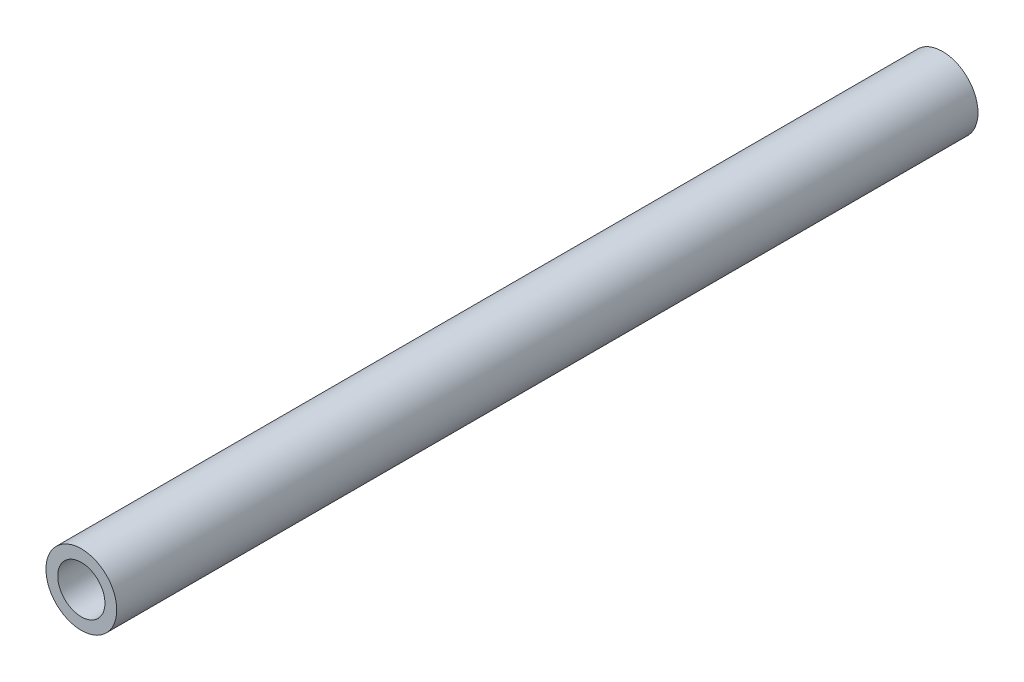
SolidWorks part; units mm, degrees
other "Ballast Support Tube 2 Left"
ref_plane "Front Plane" through (0, 0, 0) normal (0, 0, 1) x (1, 0, 0)
ref_plane "Top Plane" through (0, 0, 0) normal (0, 1, 0) x (1, 0, 0)
ref_plane "Right Plane" through (0, 0, 0) normal (1, 0, 0) x (0, 0, -1)
sketch3d "Main Profile Sketch datum points"
  point P0 (0, 0, 118)
  point P1 (10, 0, 118)
  point P2 (0, 10, 118)
ref_plane "Main Profile Sketch plane" through (0, 0, 118) normal (0, 0, 1) x (1, 0, 0)
sketch "Main Profile Sketch" plane through (0, 0, 118) normal (0, 0, 1) x (1, 0, 0)
  circle A0 centre (-90, 51.5) radius 3
  circle A1 centre (-90, 51.5) radius 2
extrude "Main Extrusion" add sketch "Main Profile Sketch" against normal blind 73 separate body
